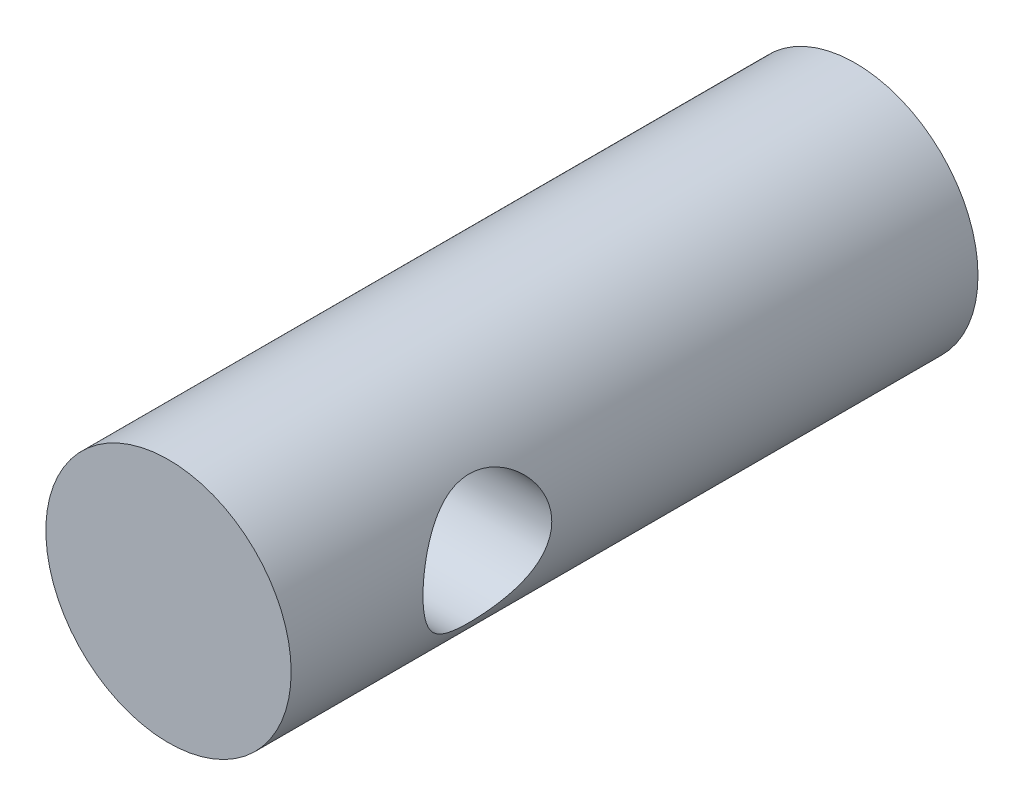
SolidWorks part; units mm, degrees
ref_plane "Ön Düzlem" through (0, 0, 0) normal (0, 0, 1) x (1, 0, 0)
ref_plane "Üst Düzlem" through (0, 0, 0) normal (0, 1, 0) x (1, 0, 0)
ref_plane "Sağ Düzlem" through (0, 0, 0) normal (1, 0, 0) x (0, 0, -1)
sketch "Çizim1" plane through (0, 0, 0) normal (0, 0, 1) x (1, 0, 0)
  circle A0 centre (0, 0) radius 10
  dimension "D1" = 20
extrude "Yükseklik-Ekstrüzyon1" add sketch "Çizim1" along normal blind 56
sketch "Çizim2" plane through (0, 0, 0) normal (1, 0, 0) x (0, 0, -1)
  line L0 (-56, -10) -> (0, -10) construction
  line L3 (-56, 10) -> (-56, -10) construction
  circle A0 centre (-40, 0) radius 5.25
  dimension "D2" = 10.5
  dimension "D1" = 10
  dimension "D3" = 16
extrude "Kes-Ekstrüzyon2" cut sketch "Çizim2" against normal through all both and the other way through all contours A0
